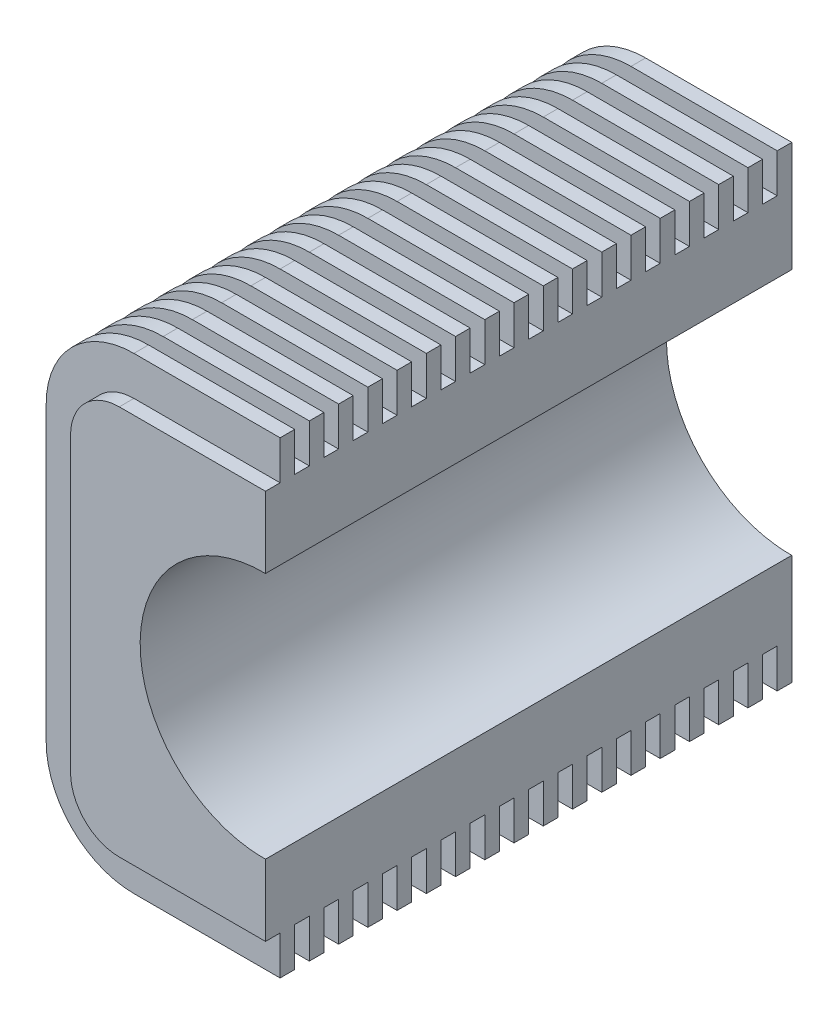
SolidWorks part; units mm, degrees
ref_plane "Płaszczyzna przednia" through (0, 0, 0) normal (0, 0, 1) x (1, 0, 0)
ref_plane "Płaszczyzna górna" through (0, 0, 0) normal (0, 1, 0) x (1, 0, 0)
ref_plane "Płaszczyzna prawa" through (0, 0, 0) normal (1, 0, 0) x (0, 0, -1)
sketch "Szkic1" plane through (0, 0, 0) normal (0, 0, 1) x (1, 0, 0)
  line L0 (0, 75) -> (-30, 75) construction
  line L1 (-40, 5) -> (-40, 65) construction
  line L2 (0, -5) -> (-30, -5) construction
  line L3 (0, 75) -> (-30, 75)
  line L4 (-40, 5) -> (-40, 65)
  line L5 (0, -5) -> (-30, -5)
  line L6 (0, -5) -> (0, 75)
  arc A0 (-30, 75) -> (-40, 65) centre (-30, 65) ccw construction
  arc A1 (-40, 5) -> (-30, -5) centre (-30, 5) ccw construction
  arc A2 (-30, 75) -> (-40, 65) centre (-30, 65) ccw
  arc A3 (-40, 5) -> (-30, -5) centre (-30, 5) ccw
extrude "Dodanie-wyciągnięcie1" add sketch "Szkic1" along normal blind 108
sketch "Szkic2" plane through (0, 0, 108) normal (0, 0, 1) x (1, 0, 0)
  ellipse E0 centre (-0.3596, 35) end of major axis (-0.3596, 9.6137) minor radius 25.3596 construction
  ellipse E1 centre (-0.3596, 35) end of major axis (-0.3596, 9.6137) minor radius 25.3596
extrude "Wytnij-wyciągnięcie1" cut sketch "Szkic2" against normal through all
sketch "Szkic3" plane through (0, 0, 0) normal (0, 0, 1) x (1, 0, 0)
  line L0 (0, 75) -> (0, 83)
  line L1 (-30, -5) -> (0, -5) construction
  line L5 (0, -13) -> (0, -5)
  line L6 (-40, 65) -> (-40, 5) construction
  line L7 (0, 75) -> (-30, 75) construction
  line L8 (-30, -13) -> (0, -13)
  line L9 (-48, 65) -> (-48, 5)
  line L10 (0, 83) -> (-30, 83)
  line L11 (-30, -13) -> (0, -13)
  line L12 (-48, 65) -> (-48, 5)
  line L13 (0, 83) -> (-30, 83)
  line L14 (-30, -5) -> (0, -5)
  line L15 (-40, 65) -> (-40, 5)
  line L16 (0, 75) -> (-30, 75)
  arc A2 (-40, 5) -> (-30, -5) centre (-30, 5) ccw construction
  arc A3 (-30, 75) -> (-40, 65) centre (-30, 65) ccw construction
  arc A4 (-48, 5) -> (-30, -13) centre (-30, 5) ccw
  arc A5 (-30, 83) -> (-48, 65) centre (-30, 65) ccw
  arc A6 (-48, 5) -> (-30, -13) centre (-30, 5) ccw
  arc A7 (-30, 83) -> (-48, 65) centre (-30, 65) ccw
  arc A8 (-40, 5) -> (-30, -5) centre (-30, 5) ccw
  arc A9 (-30, 75) -> (-40, 65) centre (-30, 65) ccw
  point P1 (-10, 82.589)
  point P6 (0, 0)
  point P8 (0, 0)
  point P9 (0, 83.1738)
  dimension "D2" = 8
extrude "Dodanie-wyciągnięcie2" add sketch "Szkic3" along normal blind 3
pattern_linear "Szyk liniowy1" count 18 spacing 6 along (0, 0, 1) of "Dodanie-wyciągnięcie2"
